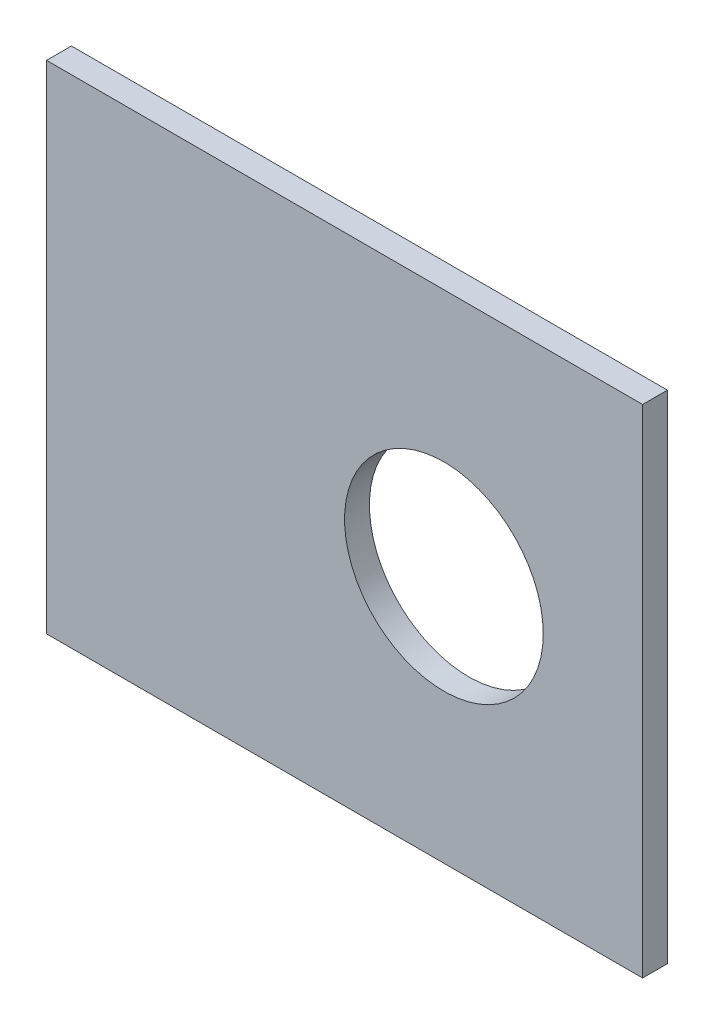
SolidWorks part; units mm, degrees
ref_plane "Front Plane" through (0, 0, 0) normal (0, 0, 1) x (1, 0, 0)
ref_plane "Top Plane" through (0, 0, 0) normal (0, 1, 0) x (1, 0, 0)
ref_plane "Right Plane" through (0, 0, 0) normal (1, 0, 0) x (0, 0, -1)
sketch "Sketch1" plane through (0, 0, 0) normal (0, 0, 1) x (1, 0, 0)
  line L1 (0, 0) -> (76.2, 0)
  line L2 (0, 0) -> (0, 63.5)
  line L3 (0, 63.5) -> (76.2, 63.5)
  line L4 (76.2, 0) -> (76.2, 63.5)
  circle A0 centre (50.8, 31.75) radius 12.7
  dimension "D3" = 25.4
  dimension "D1" = 63.5
  dimension "D2" = 76.2
  dimension "D4" = 25.4
  dimension "D5" = 31.75
extrude "Boss-Extrude1" add sketch "Sketch1" along normal blind 3.175
